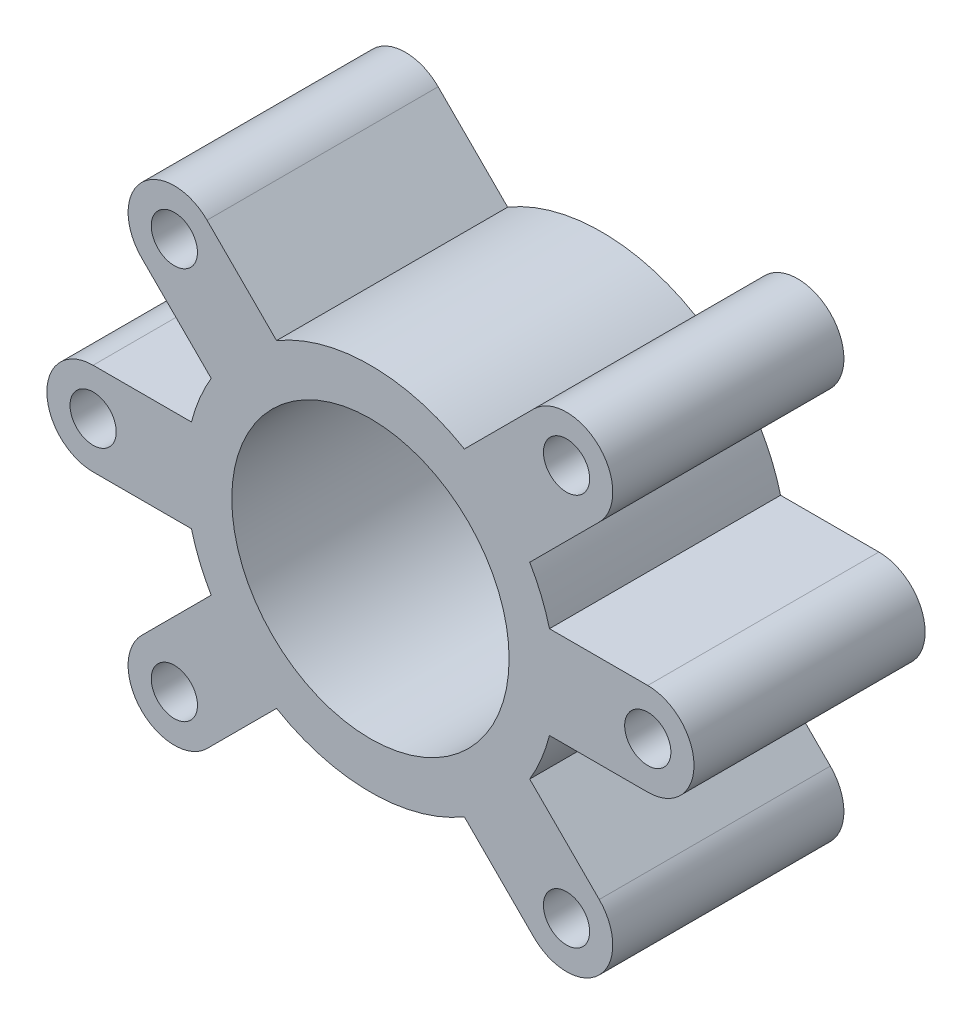
SolidWorks part; units mm, degrees
ref_plane "Front Plane" through (0, 0, 0) normal (0, 0, 1) x (1, 0, 0)
ref_plane "Top Plane" through (0, 0, 0) normal (0, 1, 0) x (1, 0, 0)
ref_plane "Right Plane" through (0, 0, 0) normal (1, 0, 0) x (0, 0, -1)
sketch "Sketch1" plane through (0, 0, 0) normal (0, 0, 1) x (1, 0, 0)
  line L0 (38.7298, 10) -> (60, 10)
  line L1 (60, -10) -> (38.7298, -10)
  line L2 (34.4572, -20.3151) -> (49.4975, -35.3553)
  line L3 (35.3553, -49.4975) -> (20.3151, -34.4572)
  line L4 (10, -38.7298) -> (10, -60) [skipped]
  line L5 (-10, -60) -> (-10, -38.7298) [skipped]
  line L6 (-20.3151, -34.4572) -> (-35.3553, -49.4975)
  line L7 (-49.4975, -35.3553) -> (-34.4572, -20.3151)
  line L8 (-38.7298, -10) -> (-60, -10)
  line L9 (-60, 10) -> (-38.7298, 10)
  line L10 (-34.4572, 20.3151) -> (-49.4975, 35.3553)
  line L11 (-35.3553, 49.4975) -> (-20.3151, 34.4572)
  line L12 (-10, 38.7298) -> (-10, 60) [skipped]
  line L13 (10, 60) -> (10, 38.7298) [skipped]
  line L14 (20.3151, 34.4572) -> (35.3553, 49.4975)
  line L15 (49.4975, 35.3553) -> (34.4572, 20.3151)
  circle A0 centre (0, 0) radius 40
  circle A1 centre (0, 0) radius 30
  arc A2 (60, 10) -> (60, -10) centre (60, 0) cw
  circle A4 centre (60, 0) radius 5
  arc A5 (49.4975, -35.3553) -> (35.3553, -49.4975) centre (42.4264, -42.4264) cw
  circle A6 centre (42.4264, -42.4264) radius 5
  arc A7 (10, -60) -> (-10, -60) centre (0, -60) cw [skipped]
  circle A8 centre (0, -60) radius 5 [skipped]
  arc A9 (-35.3553, -49.4975) -> (-49.4975, -35.3553) centre (-42.4264, -42.4264) cw
  circle A10 centre (-42.4264, -42.4264) radius 5
  arc A11 (-60, -10) -> (-60, 10) centre (-60, 0) cw
  circle A12 centre (-60, 0) radius 5
  arc A13 (-49.4975, 35.3553) -> (-35.3553, 49.4975) centre (-42.4264, 42.4264) cw
  circle A14 centre (-42.4264, 42.4264) radius 5
  arc A15 (-10, 60) -> (10, 60) centre (0, 60) cw [skipped]
  circle A16 centre (0, 60) radius 5 [skipped]
  arc A17 (35.3553, 49.4975) -> (49.4975, 35.3553) centre (42.4264, 42.4264) cw
  circle A18 centre (42.4264, 42.4264) radius 5
  point P55 (0, 0)
  dimension "D1" = 80
  dimension "D2" = 60
  dimension "D3" = 8
  dimension "D4" = 10
  dimension "D5" = 10
extrude "Boss-Extrude1" add sketch "Sketch1" along normal blind 50 contours A0 A1 | A13 L10 A0 L11 A14 | A11 L8 A0 L9 A12 | A9 L6 A0 L7 A10 | A5 L2 A0 L3 A6 | A2 L0 A0 L1 A4 | A17 L14 A0 L15 A18
